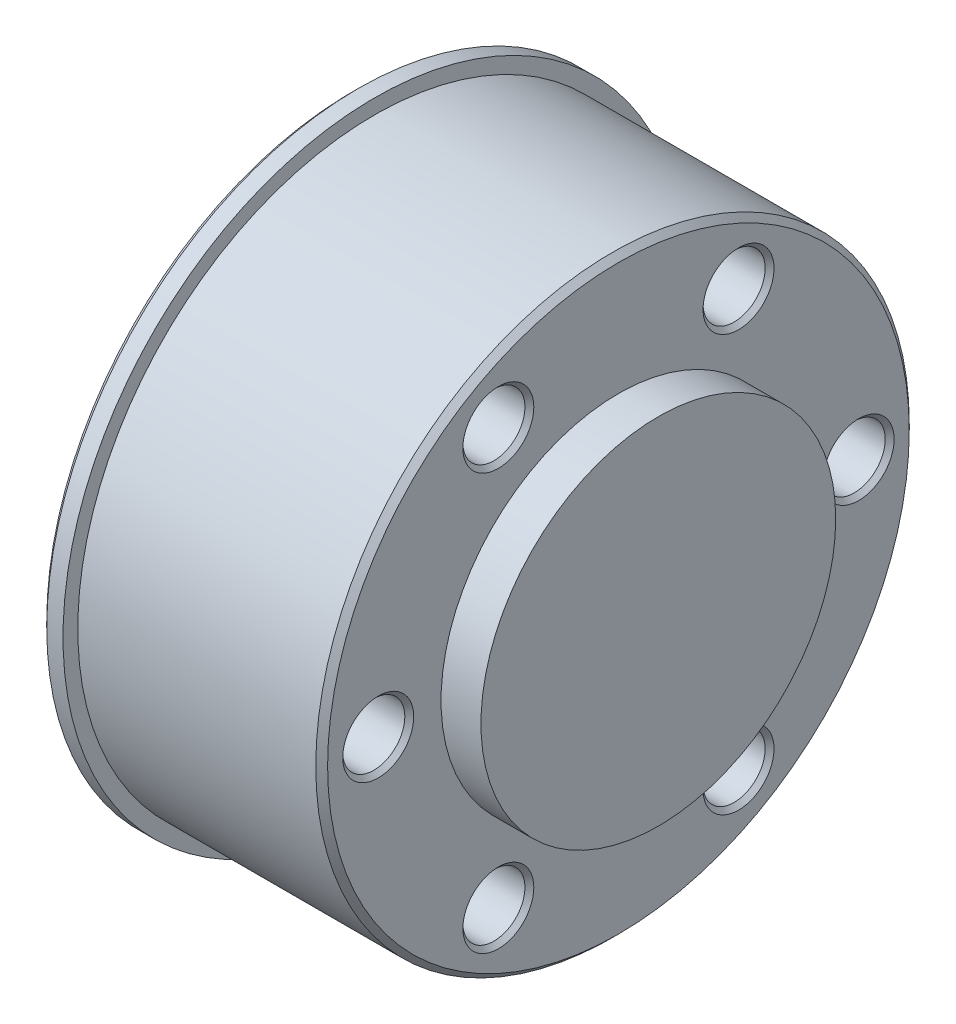
SolidWorks part; units mm, degrees
ref_plane "Front Plane" through (0, 0, 0) normal (0, 0, 1) x (1, 0, 0)
ref_plane "Top Plane" through (0, 0, 0) normal (0, 1, 0) x (1, 0, 0)
ref_plane "Right Plane" through (0, 0, 0) normal (1, 0, 0) x (0, 0, -1)
sketch "Sketch2" plane through (0, 0, 0) normal (0, 1, 0) x (1, 0, 0)
  line L0 (0, 0) -> (0, 12)
  line L1 (0, 12) -> (-2.7, 12)
  line L2 (-2.7, 12) -> (-2.7, 20.075)
  line L3 (-2.7, 20.075) -> (-19.2, 20.075)
  line L4 (-19.2, 20.075) -> (-19.2, 21.075)
  line L5 (-19.2, 21.075) -> (-20.7, 21.075)
  line L6 (-20.7, 21.075) -> (-20.7, 17.7278)
  line L7 (0, 0) -> (-41.2311, 0) construction
  line L11 (-20.7, 14.575) -> (-20.7, 8.1)
  line L12 (-20.7, 8.1) -> (-15.7, 8.1)
  line L13 (-15.7, 8.1) -> (-15.7, 6)
  line L14 (-15.7, 6) -> (-13.7, 6)
  line L15 (-13.7, 6) -> (-13.7, 0)
  line L16 (-13.7, 0) -> (0, 0)
  line L17 (-20.7, 17.7278) -> (-20.7, 14.575)
  dimension "D1" = 12
  dimension "D2" = 2.7
  dimension "D3" = 8.075
  dimension "D4" = 16.5
  dimension "D5" = 1
  dimension "D6" = 1.5
  dimension "D8" = 8.1
  dimension "D9" = 6
  dimension "D10" = 5
  dimension "D13" = 2
revolve "Revolve1" add sketch "Sketch2" angle 360 about L7
sketch "Sketch3" plane through (-20.7, 0, 0) normal (-1, 0, 0) x (0, 0, 1)
  circle A0 centre (0, 16) radius 1.625
  circle A1 centre (13.8564, 7.9047) radius 1.625
  circle A2 centre (13.7739, -8.1429) radius 1.625
  circle A3 centre (-0.165, -16.0953) radius 1.625
  circle A4 centre (-14.0214, -8) radius 1.625
  circle A5 centre (-13.9389, 8.0476) radius 1.625
  dimension "D1" = 3.25
  dimension "D3" = 16
  dimension "D2" = 6
extrude "Cut-Extrude1" cut sketch "Sketch3" against normal blind 12
sketch "Sketch4" plane through (-2.7, 0, 0) normal (1, 0, 0) x (0, 0, -1)
  line L0 (0, 0) -> (0, 20.075) construction
  line L1 (-8.125, 14.0729) -> (0, 0) construction
  circle A0 centre (-8.125, 14.0729) radius 2.1
  circle A1 centre (8.125, 14.0729) radius 2.1
  circle A2 centre (16.25, 0) radius 2.1
  circle A3 centre (8.125, -14.0729) radius 2.1
  circle A4 centre (-8.125, -14.0729) radius 2.1
  circle A5 centre (-16.25, 0) radius 2.1
  circle A6 centre (0, 0) radius 20.075 construction
  circle A7 centre (0, 0) radius 16.25 construction
  point P15 (0, 0)
  dimension "D1" = 4.2
  dimension "D2" = 30
  dimension "D3" = 6
  dimension "D4" = 16.25
extrude "Cut-Extrude2" cut sketch "Sketch4" against normal blind 10
sketch "Sketch5" plane through (-2.7, 0, 0) normal (1, 0, 0) x (0, 0, -1)
  line L1 (10.0375, 17.3855) -> (-10.0375, -17.3855) construction
  circle A0 centre (0, 0) radius 20.075 construction
  circle A1 centre (0, 0) radius 20.075 construction
chamfer "Chamfer1" distance 0.4 angle 45 1 edges at (-2.7, 0, -20.075)
chamfer "Chamfer2" distance 0.4 angle 45 1 edges at (-20.7, 0, -8.1)
chamfer "Chamfer3" distance 0.4 angle 45 6 edges at (-20.7, 16, 1.625) (-20.7, 8.0476, -12.3139) (-20.7, -8, -12.3964) (-20.7, -16.0953, 1.46) (-20.7, -8.1429, 15.3989) (-20.7, 7.9047, 15.4814)
chamfer "Chamfer4" distance 0.3 angle 45 6 edges at (-2.7, -14.0729, -10.225) (-2.7, 0, -18.35) (-2.7, 14.0729, -10.225) (-2.7, 14.0729, 6.025) (-2.7, -14.0729, 6.025) (-2.7, 0, 14.15)
chamfer "Chamfer5" distance 0.4 angle 45 1 edges at (-20.7, 0, -21.075)
